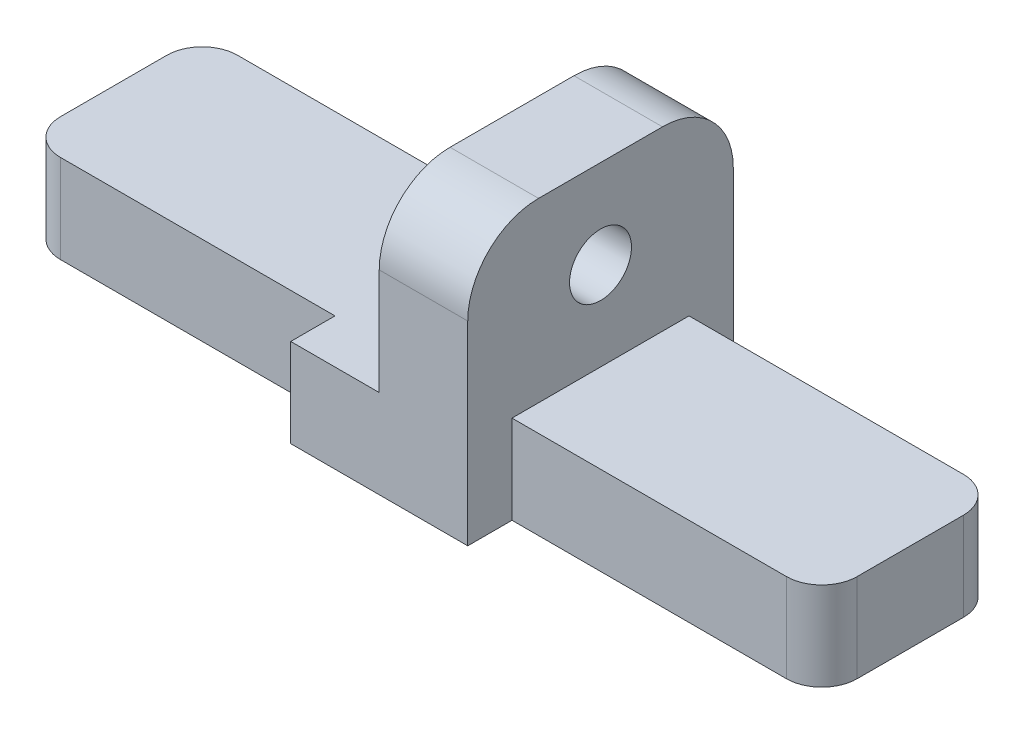
SolidWorks part; units mm, degrees
ref_plane "前视基准面" through (0, 0, 0) normal (0, 0, 1) x (1, 0, 0)
ref_plane "上视基准面" through (0, 0, 0) normal (0, 1, 0) x (1, 0, 0)
ref_plane "右视基准面" through (0, 0, 0) normal (1, 0, 0) x (0, 0, -1)
other "Configuration Table"
sketch "草图3" plane through (0, 0, 0) normal (0, 1, 0) x (1, 0, 0)
  line L1 (-22.5, 5) -> (22.5, 5)
  line L2 (-22.5, 5) -> (-22.5, -5)
  line L3 (-22.5, -5) -> (22.5, -5)
  line L4 (22.5, 5) -> (22.5, -5)
  line L5 (-22.5, 5) -> (22.5, -5) construction
  line L6 (-22.5, -5) -> (22.5, 5) construction
  point P0 (0, 0)
  dimension "D1" = 45
  dimension "D2" = 10
extrude "凸台-拉伸2" add sketch "草图3" along normal blind 5
sketch "草图4" plane through (0, 5, 0) normal (0, 1, 0) x (1, 0, 0)
  line L1 (-5, 7.5) -> (5, 7.5)
  line L2 (-5, 7.5) -> (-5, -7.5)
  line L3 (-5, -7.5) -> (5, -7.5)
  line L4 (5, 7.5) -> (5, -7.5)
  line L5 (-5, 7.5) -> (5, -7.5) construction
  line L6 (-5, -7.5) -> (5, 7.5) construction
  point P0 (0, 0)
  dimension "D1" = 10
  dimension "D2" = 15
extrude "凸台-拉伸3" add sketch "草图4" along normal blind 10 and the other way up to surface other way up to face at (0, 0, 0)
sketch "草图5" plane through (-5, 0, 0) normal (-1, 0, 0) x (0, 0, 1)
  line L1 (0, 17.7731) -> (0, -1.9609) construction
  line L2 (-7.5, 10) -> (7.5, 10)
  line L3 (-7.5, 10) -> (7.5, 10) construction
  circle A0 centre (0, 10) radius 1.75
  dimension "D2" = 3.5
  dimension "D1" = 5
extrude "切除-拉伸1" cut sketch "草图5" against normal blind 10
fillet "圆角2" radius 2 4 edges at (-22.5, 2.5, 5) (-22.5, 2.5, -5) (22.5, 2.5, -5) (22.5, 2.5, 5)
fillet "圆角1" radius 4 2 edges at (0, 15, 7.5) (0, 15, -7.5)
sketch "草图8" plane through (-5, 0, 0) normal (-1, 0, 0) x (0, 0, 1)
  line L5 (-10, 15) -> (10, 15)
  line L6 (-10, 15) -> (-10, 5)
  line L7 (-10, 5) -> (10, 5)
  line L8 (10, 15) -> (10, 5)
  line L9 (-10, 15) -> (10, 5) construction
  line L10 (-10, 5) -> (10, 15) construction
  point P4 (0, 10)
  dimension "D1" = 10
  dimension "D2" = 20
extrude "切除-拉伸2" cut sketch "草图8" against normal blind 5
